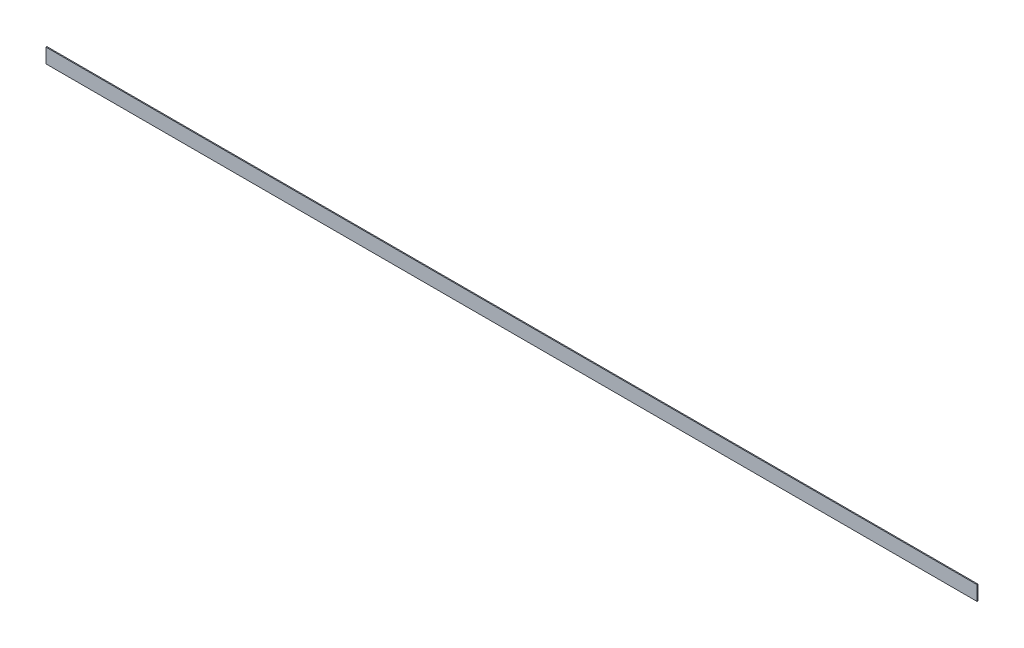
SolidWorks part; units mm, degrees
material "Silicon Rubber"
ref_plane "Front Plane" through (0, 0, 0) normal (0, 0, 1) x (1, 0, 0)
ref_plane "Top Plane" through (0, 0, 0) normal (0, 1, 0) x (1, 0, 0)
ref_plane "Right Plane" through (0, 0, 0) normal (1, 0, 0) x (0, 0, -1)
sketch "Sketch1" plane through (0, 0, 0) normal (0, 0, 1) x (1, 0, 0)
  line L1 (0, 0) -> (1219.2, 0)
  line L2 (0, 0) -> (0, 19.05)
  line L3 (0, 19.05) -> (1219.2, 19.05)
  line L4 (1219.2, 0) -> (1219.2, 19.05)
  dimension "D1" = 1219.2
  dimension "D2" = 19.05
extrude "Boss-Extrude1" add sketch "Sketch1" along normal blind 1.27
ref_plane "Plane1" through (0, 9.525, 0) normal (0, 1, 0) x (1, 0, 0)
